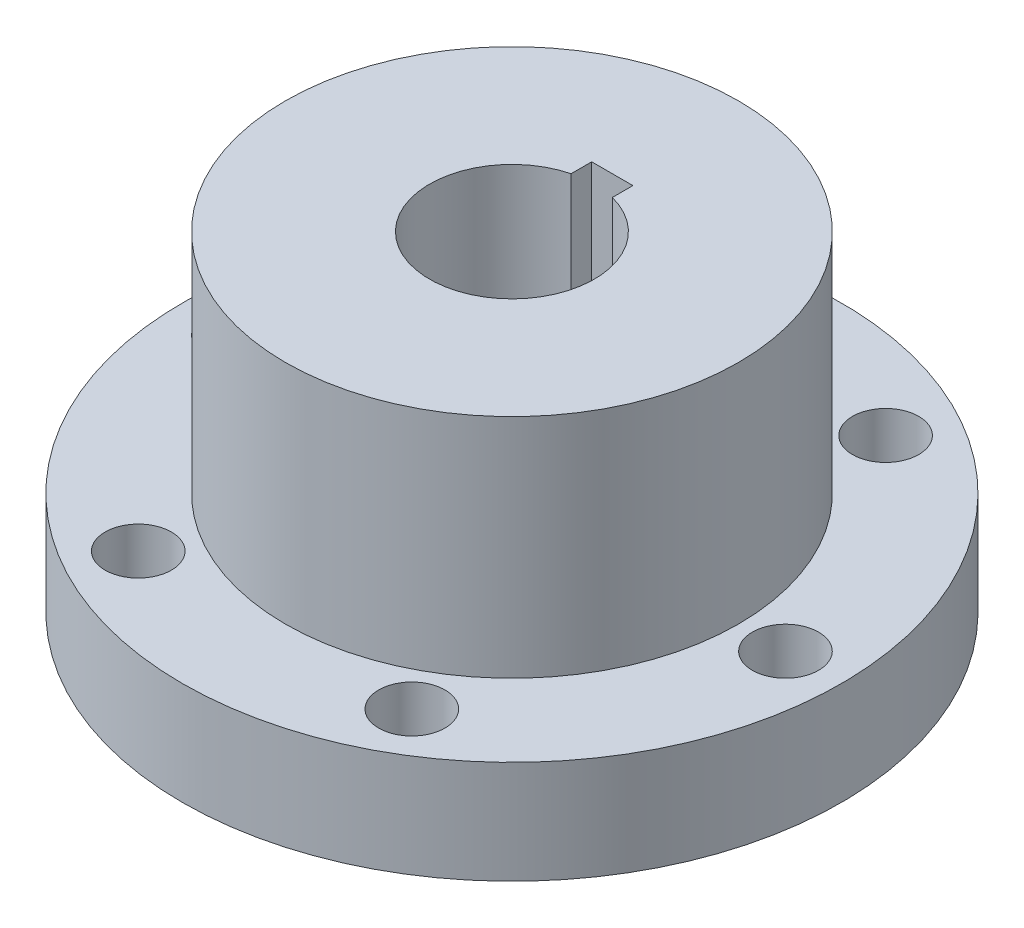
SolidWorks part; units mm, degrees
ref_plane "Front Plane" through (0, 0, 0) normal (0, 0, 1) x (1, 0, 0)
ref_plane "Top Plane" through (0, 0, 0) normal (0, 1, 0) x (1, 0, 0)
ref_plane "Right Plane" through (0, 0, 0) normal (1, 0, 0) x (0, 0, -1)
sketch "Sketch1" plane through (0, 0, 0) normal (0, 1, 0) x (1, 0, 0)
  circle A0 centre (0, 0) radius 25.4
  dimension "D1" = 50.8
extrude "Boss-Extrude1" add sketch "Sketch1" along normal blind 25.4 contours A0
sketch "Sketch2" plane through (0, 25.4, 0) normal (0, 1, 0) x (1, 0, 0)
  circle A0 centre (0, 0) radius 17.4625
  circle A1 centre (0, 0) radius 25.4 construction
  circle A2 centre (0, 0) radius 25.4
  dimension "D1" = 34.925
extrude "Cut-Extrude1" cut sketch "Sketch2" against normal blind 17.4625
sketch "Sketch3" plane through (0, 25.4, 0) normal (0, 1, 0) x (1, 0, 0)
  line L1 (-1.5875, 6.1484) -> (1.5875, 6.1484)
  line L2 (-1.5875, 6.1484) -> (-1.5875, 7.7359)
  line L3 (-1.5875, 7.7359) -> (1.5875, 7.7359)
  line L4 (1.5875, 6.1484) -> (1.5875, 7.7359)
  circle A0 centre (0, 0) radius 6.35
  dimension "D1" = 12.7
  dimension "D2" = 3.175
  dimension "D3" = 1.5875
extrude "Cut-Extrude2" cut sketch "Sketch3" against normal through all contours L1 A0 | A0 L4 L3 L2 | L1 A0
sketch "Sketch9" plane through (0, 7.9375, 0) normal (0, 1, 0) x (1, 0, 0)
  point P0 (21.082, 0)
  point P5 (10.541, -18.2575)
  point P6 (-10.541, -18.2575)
  point P7 (-21.082, 0)
  point P8 (-10.541, 18.2575)
  point P9 (10.541, 18.2575)
  point P10 (0, 0)
  dimension "D1" = 21.082
  dimension "D2" = 6
hole_wizard "#10 Clearance Hole1" positions "3DSketch3" profile "Sketch10" hole size "#10" standard "ANSI Inch" end condition through all
sketch3d "3DSketch3"
  point P0 (21.082, 7.9375, 0)
  point P3 (10.541, 7.9375, -18.2575)
  point P6 (-10.541, 7.9375, -18.2575)
  point P9 (-21.082, 7.9375, 0)
  point P12 (-10.541, 7.9375, 18.2575)
  point P15 (10.541, 7.9375, 18.2575)
sketch "Sketch10" plane through (21.082, 7.9375, 0) normal (1, 0, 0) x (0, 0, 1)
  line L0 (0, 0) -> (0, 7.9375)
  line L1 (0, 7.9375) -> (2.5527, 7.9375)
  line L2 (2.5527, 7.9375) -> (2.5527, 0)
  line L5 (2.5527, 0) -> (0, 0)
  line L11 (0, -6.35) -> (0, 107.95) construction
  dimension "Thru Hole Dia." = 5.1054
  dimension "Thru Hole Depth" = 7.9375
